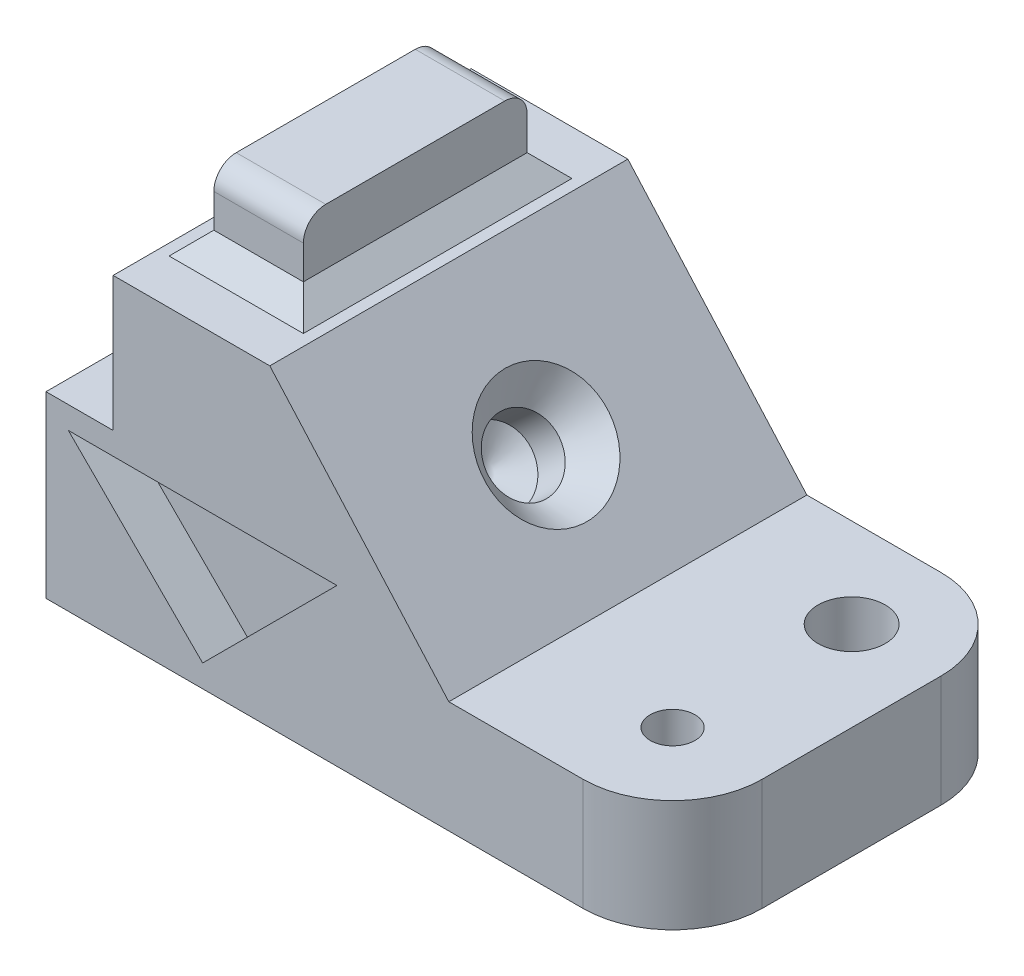
SolidWorks part; units mm, degrees
ref_plane "Front Plane" through (0, 0, 0) normal (0, 0, 1) x (1, 0, 0)
ref_plane "Top Plane" through (0, 0, 0) normal (0, 1, 0) x (1, 0, 0)
ref_plane "Right Plane" through (0, 0, 0) normal (1, 0, 0) x (0, 0, -1)
sketch "Sketch1" plane through (0, 0, 0) normal (0, 0, 1) x (1, 0, 0)
  line L0 (0, 0) -> (0, 50.8)
  line L1 (0, 50.8) -> (19.05, 50.8)
  line L2 (19.05, 50.8) -> (19.05, 88.9)
  line L3 (19.05, 88.9) -> (63.5, 88.9)
  line L4 (63.5, 88.9) -> (114.3, 31.75)
  line L5 (114.3, 31.75) -> (177.8, 31.75)
  line L6 (177.8, 31.75) -> (177.8, 0)
  line L7 (177.8, 0) -> (0, 0)
  dimension "D1" = 31.75
  dimension "D2" = 63.5
  dimension "D3" = 44.45
  dimension "D4" = 177.8
  dimension "D5" = 19.05
  dimension "D6" = 50.8
  dimension "D7" = 88.9
extrude "Boss-Extrude1" add sketch "Sketch1" along normal blind 101.6
ref_plane "Plane1" through (41.275, 0, 0) normal (-1, 0, 0) x (0, 0, 1)
sketch "Sketch2" plane through (41.275, 0, 0) normal (-1, 0, 0) x (0, 0, 1)
  line L0 (0, 0) -> (50.8, 0) construction
  line L1 (101.6, 0) -> (0, 0) construction
  line L2 (50.8, 0) -> (50.8, 111.125) construction
  line L3 (101.6, 88.9) -> (0, 88.9) construction
  line L4 (25.4, 111.125) -> (76.2, 111.125)
  line L5 (82.55, 104.775) -> (82.55, 88.9)
  line L6 (82.55, 88.9) -> (19.05, 88.9)
  line L7 (19.05, 104.775) -> (19.05, 88.9)
  arc A0 (76.2, 111.125) -> (82.55, 104.775) centre (76.2, 104.775) cw
  arc A1 (25.4, 111.125) -> (19.05, 104.775) centre (25.4, 104.775) ccw
  point P17 (50.8, 88.9)
  dimension "D3" = 6.35
  dimension "D1" = 22.225
  dimension "D2" = 31.75
extrude "Boss-Extrude2" add sketch "Sketch2" along normal mid plane 25.4
chamfer "Chamfer1" distance 6.35 angle 45 4 edges at (28.575, 88.9, 50.8) (41.275, 88.9, 19.05) (53.975, 88.9, 50.8) (41.275, 88.9, 82.55)
fillet "Fillet1" radius 25.4 2 edges at (177.8, 15.875, 101.6) (177.8, 15.875, 0)
sketch "Sketch4" plane through (0, 0, 0) normal (0, 1, 0) x (1, 0, 0)
  line L0 (152.4, 0) -> (152.4, -25.4) construction
  line L1 (177.8, -76.2) -> (152.4, -76.2) construction
  line L3 (177.8, -25.4) -> (152.4, -25.4) construction
  line L4 (152.4, -76.2) -> (152.4, -101.6) construction
sketch "Sketch5" plane through (0, 0, 101.6) normal (0, 0, 1) x (1, 0, 0)
  line L0 (6.35, 44.45) -> (82.55, 44.45) construction
  line L1 (0, 50.8) -> (0, 0) construction
  line L2 (82.55, 44.45) -> (82.55, 6.35) construction
  line L3 (0, 0) -> (152.4, 0) construction
  line L4 (6.35, 44.45) -> (6.35, 6.35) construction
  line L5 (6.35, 6.35) -> (82.55, 6.35) construction
  line L6 (44.45, 6.35) -> (44.45, 44.45) construction
  line L7 (6.35, 44.45) -> (82.55, 44.45)
  line L8 (82.55, 44.45) -> (44.45, 6.35)
  line L9 (44.45, 6.35) -> (6.35, 44.45)
  dimension "D1" = 38.1
  dimension "D2" = 76.2
  dimension "D3" = 6.35
  dimension "D4" = 6.35
extrude "Cut-Extrude2" cut sketch "Sketch5" against normal blind 12.7
sketch "Sketch6" plane through (79.6159, 70.7697, 0) normal (0.7474, 0.6644, 0) x (0, 0, -1)
  line L0 (-101.6, -52.2065) -> (-101.6, -17.2815) construction
  line L1 (-101.6, -52.2065) -> (-101.6, 24.2576) construction
  line L2 (-101.6, -17.2815) -> (-50.8, -17.2815) construction
  line L3 (-101.6, -52.2065) -> (0, -52.2065) construction
  dimension "D1" = 50.8
  dimension "D2" = 34.925
sketch "Sketch7" plane through (79.6159, 70.7697, 0) normal (0.7474, 0.6644, 0) x (0, 0, -1)
  point P0 (-50.8, -17.2815)
sketch "Sketch8" plane through (79.6159, 70.7697, 0) normal (0.7474, 0.6644, 0) x (0, 0, -1)
  point P0 (-50.8, -17.2815)
hole_wizard "CSK for 3/4 Flat Head Machine Screw1" positions "Sketch8" profile "Sketch9" countersink size "3/4" standard "ANSI Inch"
sketch "Sketch9" plane through (91.0971, 57.8533, 50.8) normal (0, 0, 1) x (-0.6644, 0.7474, 0)
  line L0 (0, 0) -> (0, 25.0113)
  line L1 (0, 25.0113) -> (9.9212, 19.05)
  line L2 (9.9212, 19.05) -> (9.9212, 8.6752)
  line L3 (9.9212, 8.6752) -> (17.4625, 0)
  line L5 (17.4625, 0) -> (0, 0)
  line L6 (-9.9212, 8.6752) -> (-17.4625, 0) construction
  line L10 (0, 25.0113) -> (-9.9212, 19.05) construction
  line L11 (0, -6.35) -> (0, 107.95) construction
  dimension "Hole Dia." = 19.8425
  dimension "Hole Depth" = 19.05
  dimension "Near C'Sink Dia." = 34.925
  dimension "Near C'Sink Angle" = 82
  dimension "Drill Angle" = 118
sketch "Sketch10" plane through (0, 0, 0) normal (0, -1, 0) x (-1, 0, 0)
  point P0 (-152.4, -25.4)
hole_wizard "3/4 (0.75) Diameter Hole1" positions "Sketch10" profile "Sketch11" hole size "3/4" standard "ANSI Inch" end condition through all
sketch "Sketch11" plane through (152.4, 0, 25.4) normal (1, 0, 0) x (0, 0, -1)
  line L0 (0, 0) -> (0, 111.125)
  line L1 (0, 111.125) -> (9.525, 111.125)
  line L2 (9.525, 111.125) -> (9.525, 0)
  line L5 (9.525, 0) -> (0, 0)
  line L11 (0, -6.35) -> (0, 107.95) construction
  dimension "Thru Hole Dia." = 19.05
  dimension "Thru Hole Depth" = 111.125
sketch "Sketch12" plane through (0, 0, 0) normal (0, -1, 0) x (-1, 0, 0)
  point P0 (-152.4, -76.2)
hole_wizard "1/2 (0.5) Diameter Hole1" positions "Sketch12" profile "Sketch13" hole size "1/2" standard "ANSI Inch" end condition through all
sketch "Sketch13" plane through (152.4, 0, 76.2) normal (1, 0, 0) x (0, 0, -1)
  line L0 (0, 0) -> (0, 111.125)
  line L1 (0, 111.125) -> (6.35, 111.125)
  line L2 (6.35, 111.125) -> (6.35, 0)
  line L5 (6.35, 0) -> (0, 0)
  line L11 (0, -6.35) -> (0, 107.95) construction
  dimension "Thru Hole Dia." = 12.7
  dimension "Thru Hole Depth" = 111.125
